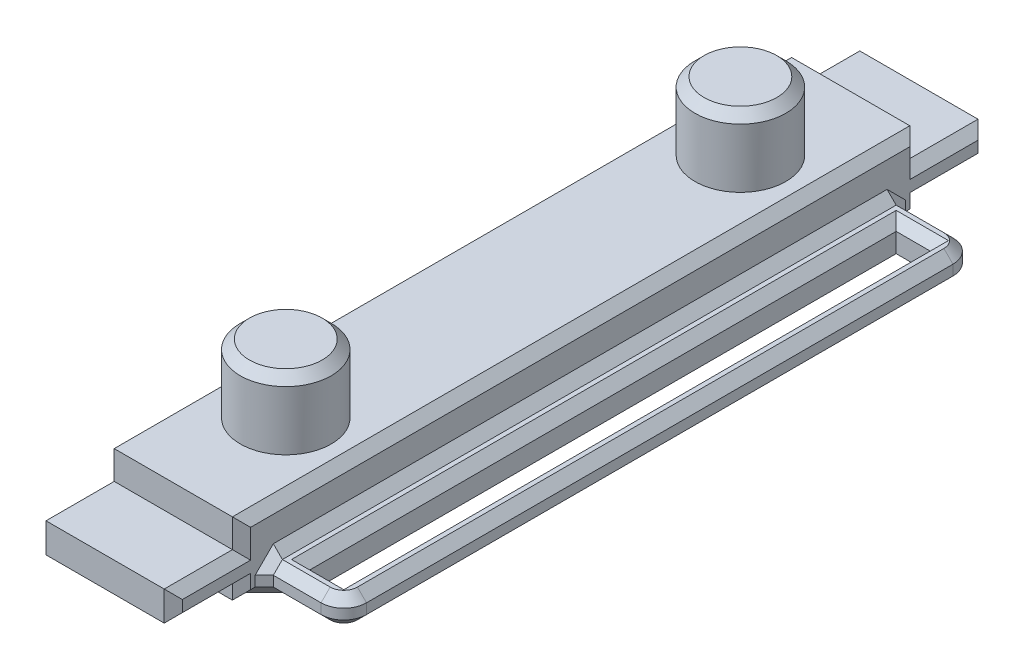
SolidWorks part; units mm, degrees
ref_plane "Front Plane" through (0, 0, 0) normal (0, 0, 1) x (1, 0, 0)
ref_plane "Top Plane" through (0, 0, 0) normal (0, 1, 0) x (1, 0, 0)
ref_plane "Right Plane" through (0, 0, 0) normal (1, 0, 0) x (0, 0, -1)
sketch "Sketch1" plane through (0, 0, 0) normal (1, 0, 0) x (0, 0, -1)
  line L0 (-30.0963, 4.0963) -> (-30.0963, 1.5963) construction
  line L1 (-30.0963, 1.5963) -> (-36.0963, 1.5963) construction
  line L2 (-36.0963, 1.5963) -> (-36.0963, -1.4037) construction
  line L3 (-36.0963, -1.4037) -> (-30.0963, -1.4037) construction
  line L4 (-30.0963, -1.4037) -> (-30.0963, -2.6537) construction
  line L5 (-0.0963, -3.9037) -> (-0.0963, 4.0963) construction
  line L6 (29.9037, -1.4037) -> (29.9037, -2.6537) construction
  line L7 (35.9037, -1.4037) -> (29.9037, -1.4037) construction
  line L8 (35.9037, 1.5963) -> (35.9037, -1.4037) construction
  line L9 (29.9037, 1.5963) -> (35.9037, 1.5963) construction
  line L10 (29.9037, 4.0963) -> (29.9037, 1.5963) construction
  line L11 (-30.0963, 4.0963) -> (29.9037, 4.0963) construction
  line L12 (-30.0963, -2.6537) -> (29.9037, -2.6537) construction
  line L13 (-29.8963, 3.8963) -> (-29.8963, 1.3963)
  line L14 (-29.8963, 1.3963) -> (-35.8963, 1.3963)
  line L15 (-35.8963, 1.3963) -> (-35.8963, -1.2037)
  line L16 (-35.8963, -1.2037) -> (-29.8963, -1.2037)
  line L17 (-29.8963, -1.2037) -> (-29.8963, -2.4537)
  line L18 (-29.8963, -2.4537) -> (29.7037, -2.4537)
  line L19 (29.7037, -1.2037) -> (29.7037, -2.4537)
  line L20 (35.7037, -1.2037) -> (29.7037, -1.2037)
  line L21 (35.7037, 1.3963) -> (35.7037, -1.2037)
  line L22 (29.7037, 1.3963) -> (35.7037, 1.3963)
  line L23 (29.7037, 3.8963) -> (29.7037, 1.3963)
  line L24 (-29.8963, 3.8963) -> (29.7037, 3.8963)
  dimension "D1" = 6
  dimension "D2" = 3
  dimension "D3" = 2.5
  dimension "D4" = 0.2
extrude "Boss-Extrude1" add sketch "Sketch1" along normal blind 12
sketch "Sketch2" plane through (0, 3.8963, 0) normal (0, 1, 0) x (1, 0, 0)
  line L0 (12, 29.7037) -> (12, -29.8963) construction
  circle A0 centre (6, -20) radius 4
  circle A1 centre (6, 20) radius 4
  dimension "D3" = 8
  dimension "D4" = 8
  dimension "D1" = 40
  dimension "D2" = 20
  dimension "D5" = 6
  dimension "D6" = 6
extrude "Boss-Extrude2" add sketch "Sketch2" along normal blind 6
sketch "Sketch3" plane through (12, 0, 0) normal (1, 0, 0) x (0, 0, -1)
  line L1 (-27.8963, -2.4537) -> (27.7037, -2.4537)
  line L3 (-27.8963, 0.0463) -> (27.7037, 0.0463)
  line L5 (-27.8963, -2.3698) -> (27.7037, -0.0376) construction
  line L6 (-27.8963, -0.0376) -> (27.7037, -2.3698) construction
  line L7 (-27.8963, 0.0463) -> (-27.8963, -2.4537)
  line L8 (27.7037, 0.0463) -> (27.7037, -2.4537)
  line L9 (29.7037, 3.8963) -> (-29.8963, 3.8963) construction
  point P4 (-0.0963, -1.2037)
  dimension "D1" = 2
  dimension "D2" = 29.8
  dimension "D3" = 3.85
  dimension "D4" = 3.9339
  dimension "D5" = 5.1
  dimension "D7" = 6.35
extrude "Boss-Extrude3" add sketch "Sketch3" along normal blind 7
sketch "Sketch5" plane through (0, 0.0463, 0) normal (0, 1, 0) x (1, 0, 0)
  line L8 (14, 25.7037) -> (14, -25.8963)
  line L9 (14, -25.8963) -> (17, -25.8963)
  line L10 (17, -25.8963) -> (17, 25.7037)
  line L11 (17, 25.7037) -> (14, 25.7037)
  line L12 (14, 25.7037) -> (14, -25.8963)
  line L13 (14, -25.8963) -> (17, -25.8963)
  line L14 (17, -25.8963) -> (17, 25.7037)
  line L15 (17, 25.7037) -> (14, 25.7037)
  dimension "D1" = 2
extrude "Cut-Extrude1" cut sketch "Sketch5" against normal through all
fillet "Fillet3" radius 2 2 edges at (19, -1.2037, -27.7037) (19, -1.2037, 27.8963)
chamfer "Chamfer1" distance 0.8 angle 45 12 edges at (0, 2.6463, 29.8963) (0, 1.3963, 32.8963) (0, 0.0963, 35.8963) (0, -1.2037, 32.8963) (0, -1.8287, 29.8963) (0, -2.4537, 0.0963) (0, -1.8287, -29.7037) (0, -1.2037, -32.7037) (0, 0.0963, -35.7037) (0, 1.3963, -32.7037) (0, 2.6463, -29.7037) (0, 3.8963, 0.0963)
chamfer "Chamfer2" distance 0.8 angle 45 2 edges at (6, 9.8963, 24) (6, 9.8963, -16)
chamfer "Chamfer3" distance 0.8 angle 45 30 edges at (15.5, 0.0463, 25.8963) (17, 0.0463, 0.0963) (15.5, 0.0463, -25.7037) (14, 0.0463, 0.0963) (19, -2.4537, 0.0963) (18.4142, -2.4537, 27.3105) (18.4142, -2.4537, -27.1179) (14.5, -2.4537, 27.8963) (14.5, -2.4537, -27.7037) (18.4142, 0.0463, 27.3105) (14.5, 0.0463, 27.8963) (19, 0.0463, 0.0963) (18.4142, 0.0463, -27.1179) (14.5, 0.0463, -27.7037) (12, -2.4537, 28.8963) (12, -1.8287, 29.8963) (12, -1.2037, 32.8963) (12, 0.0963, 35.8963) (12, 1.3963, 32.8963) (12, 2.6463, 29.8963) (12, 3.8963, 0.0963) (12, 2.6463, -29.7037) (12, 1.3963, -32.7037) (12, 0.0963, -35.7037) (12, -1.2037, -32.7037) (12, -1.8287, -29.7037) (12, -2.4537, -28.7037) (12, -1.2037, -27.7037) (12, 0.0463, 0.0963) (12, -1.2037, 27.8963)
